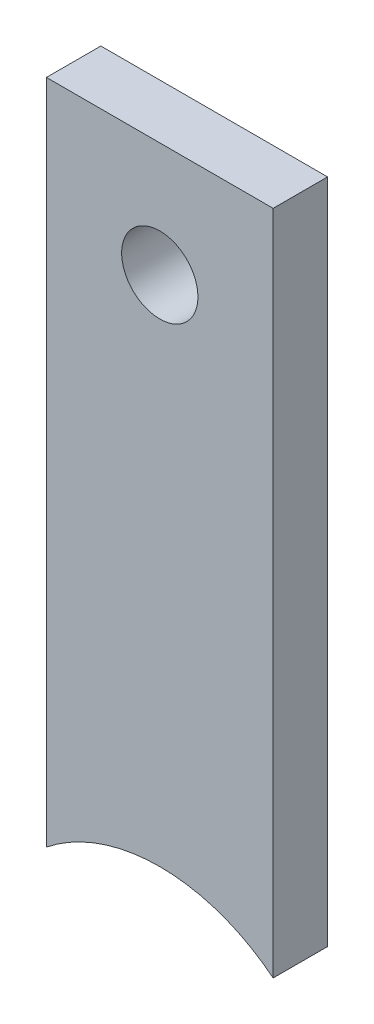
SolidWorks part; units mm, degrees
material "ASTM A36 Steel"
ref_plane "Front Plane" through (0, 0, 0) normal (0, 0, 1) x (1, 0, 0)
ref_plane "Top Plane" through (0, 0, 0) normal (0, 1, 0) x (1, 0, 0)
ref_plane "Right Plane" through (0, 0, 0) normal (1, 0, 0) x (0, 0, -1)
sketch "Sketch1" plane through (0, 0, 0) normal (0, 0, 1) x (1, 0, 0)
  line L2 (-25, -73.5) -> (-25, 73.5)
  line L3 (-25, 73.5) -> (25, 73.5)
  line L4 (25, -73.5) -> (25, 73.5)
  arc A0 (25, -73.5) -> (-25, -73.5) centre (0, -104.725) ccw
  circle A1 centre (0, 48.275) radius 8.413
  point P0 (0, 0)
  dimension "D3" = 40
  dimension "D4" = 153
  dimension "D1" = 50
  dimension "D2" = 147
extrude "Boss-Extrude1" add sketch "Sketch1" along normal blind 12
